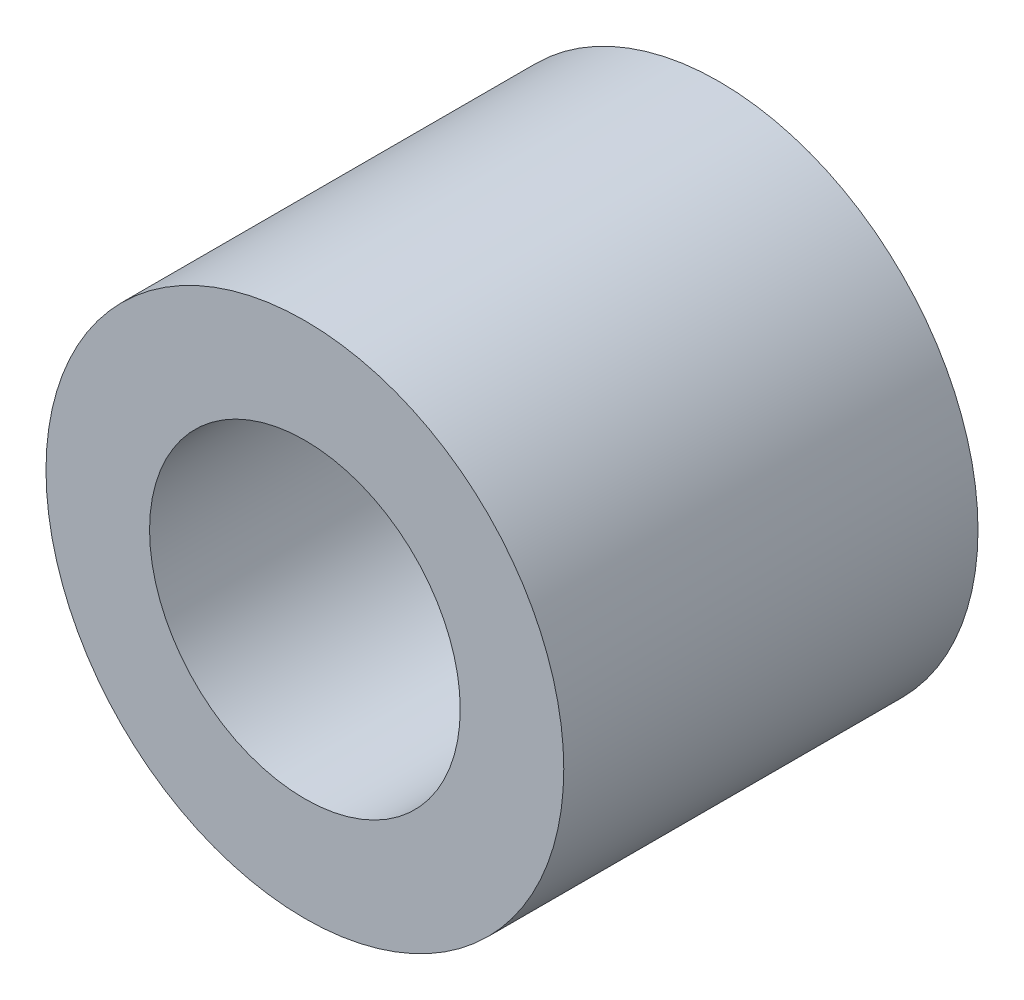
SolidWorks part; units mm, degrees
ref_plane "前视基准面" through (0, 0, 0) normal (0, 0, 1) x (1, 0, 0)
ref_plane "上视基准面" through (0, 0, 0) normal (0, 1, 0) x (1, 0, 0)
ref_plane "右视基准面" through (0, 0, 0) normal (1, 0, 0) x (0, 0, -1)
sketch "草图1" plane through (0, 0, 0) normal (0, 0, 1) x (1, 0, 0)
  circle A0 centre (0, 0) radius 5
  circle A1 centre (0, 0) radius 3
  dimension "D1" = 6
  dimension "D2" = 10
extrude "凸台-拉伸1" add sketch "草图1" against normal blind 8
